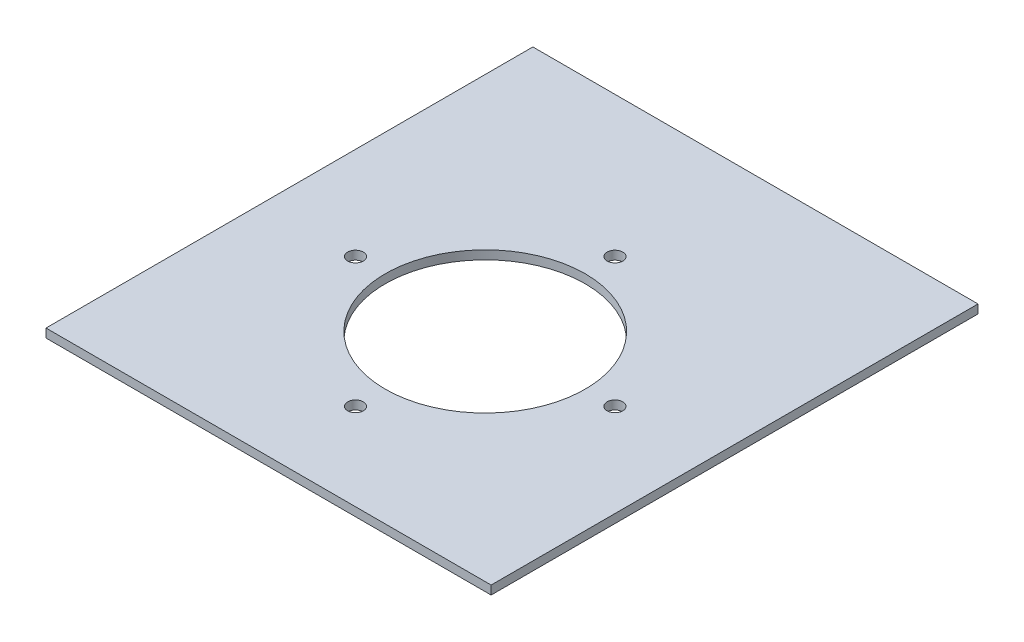
SolidWorks part; units mm, degrees
ref_plane "Płaszczyzna przednia" through (0, 0, 0) normal (0, 0, 1) x (1, 0, 0)
ref_plane "Płaszczyzna górna" through (0, 0, 0) normal (0, 1, 0) x (1, 0, 0)
ref_plane "Płaszczyzna prawa" through (0, 0, 0) normal (1, 0, 0) x (0, 0, -1)
sketch "Szkic1" plane through (0, 0, 0) normal (0, 1, 0) x (1, 0, 0)
  line L1 (0, 0) -> (256, 0)
  line L2 (0, 0) -> (0, 280)
  line L3 (0, 280) -> (256, 280)
  line L4 (256, 0) -> (256, 280)
  dimension "D1" = 280
  dimension "D2" = 256
extrude "Dodanie-wyciągnięcie1" add sketch "Szkic1" along normal blind 5
sketch "Szkic2" plane through (0, 5, 0) normal (0, 1, 0) x (1, 0, 0)
  line L0 (128, 0) -> (128, 280) construction
  line L1 (0, 0) -> (256, 0) construction
  line L2 (256, 280) -> (0, 280) construction
  line L3 (128, 199.2) -> (128, 50) construction
  circle A5 centre (128, 124.6) radius 57.5
  circle A6 centre (128, 124.6) radius 74.6 construction
  circle A7 centre (128, 199.2) radius 4.5
  circle A8 centre (202.6, 124.6) radius 4.5
  circle A9 centre (128, 50) radius 4.5
  circle A10 centre (53.4, 124.6) radius 4.5
  point P21 (128, 124.6)
  dimension "D1" = 149.2
  dimension "D5" = 115
  dimension "D3" = 9
  dimension "D2" = 124.6
  dimension "D4" = 4
extrude "Wytnij-wyciągnięcie1" cut sketch "Szkic2" against normal blind 5
